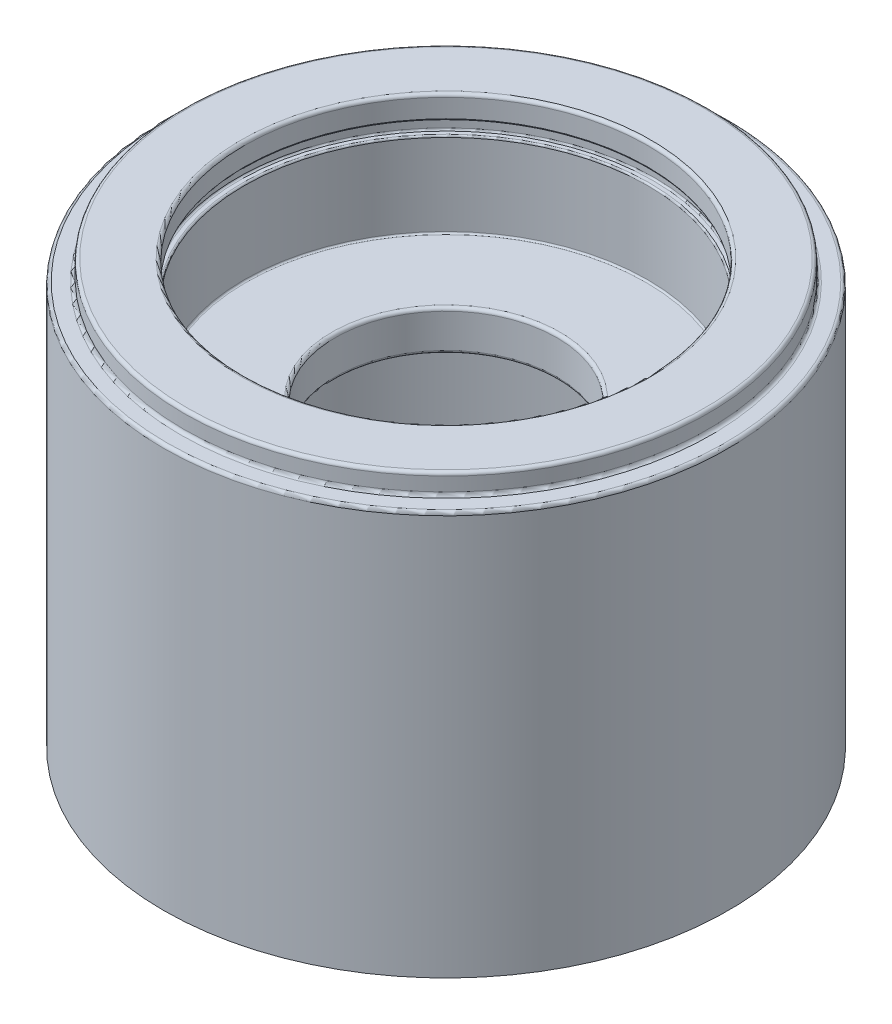
SolidWorks part; units mm, degrees
ref_plane "Спереди" through (0, 0, 0) normal (0, 0, 1) x (1, 0, 0)
ref_plane "Сверху" through (0, 0, 0) normal (0, 1, 0) x (1, 0, 0)
ref_plane "Справа" through (0, 0, 0) normal (1, 0, 0) x (0, 0, -1)
sketch "Эскиз1" plane through (0, 0, 0) normal (0, 1, 0) x (1, 0, 0)
  circle A0 centre (0, 0) radius 70
  circle A1 centre (0, 0) radius 65
  dimension "D1" = 140
  dimension "D2" = 130
extrude "Бобышка-Вытянуть1" add sketch "Эскиз1" along normal blind 105
sketch "Эскиз2" plane through (0, 105, 0) normal (0, 1, 0) x (1, 0, 0)
  circle A0 centre (0, 0) radius 65
  circle A1 centre (0, 0) radius 27.5
  dimension "D1" = 130
  dimension "D2" = 55
extrude "Бобышка-Вытянуть2" add sketch "Эскиз2" against normal blind 40
sketch "Эскиз3" plane through (0, 105, 0) normal (0, 1, 0) x (1, 0, 0)
  circle A0 centre (0, 0) radius 50
  circle A1 centre (0, 0) radius 27.5
  dimension "D1" = 100
  dimension "D2" = 55
extrude "Вырез-Вытянуть2" cut sketch "Эскиз3" against normal blind 30
sketch "Эскиз4" plane through (0, 0, 0) normal (0, 0, 1) x (1, 0, 0)
  line L0 (0, 105) -> (0, 0) construction
  line L1 (0, 96) -> (-50, 96) construction
  line L3 (-50, 96) -> (-51.75, 96)
  line L4 (-50, 96) -> (-50, 99.2)
  line L6 (50, 105) -> (-50, 105) construction
  line L14 (-50, 99.2) -> (-51.75, 99.2)
  line L15 (-51.75, 96) -> (-51.75, 99.2)
  dimension "D1" = 9
  dimension "D2" = 50
  dimension "D3" = 1.75
  dimension "D4" = 3.2
revolve "Вырез-Повернуть1" cut sketch "Эскиз4" angle 360 about L0
fillet "Скругление2" radius 0.4 4 edges at (0, 99.2, 50) (0, 96, 51.75) (0, 96, 50) (0, 75, 50)
fillet "Скругление3" radius 0.4 1 edges at (0, 99.2, 51.75)
sketch "Эскиз6" plane through (0, 105, 0) normal (0, 1, 0) x (1, 0, 0)
  circle A0 centre (0, 0) radius 70
  circle A1 centre (0, 0) radius 65
  dimension "D1" = 140
  dimension "D2" = 130
extrude "Вырез-Вытянуть3" cut sketch "Эскиз6" against normal blind 5
fillet "Скругление4" radius 0.8 4 edges at (0, 105, 50) (0, 105, 65) (0, 100, 65) (0, 100, 70)
fillet "Скругление5" radius 0.8 3 edges at (0, 65, 65) (0, 65, 27.5) (0, 75, 27.5)
